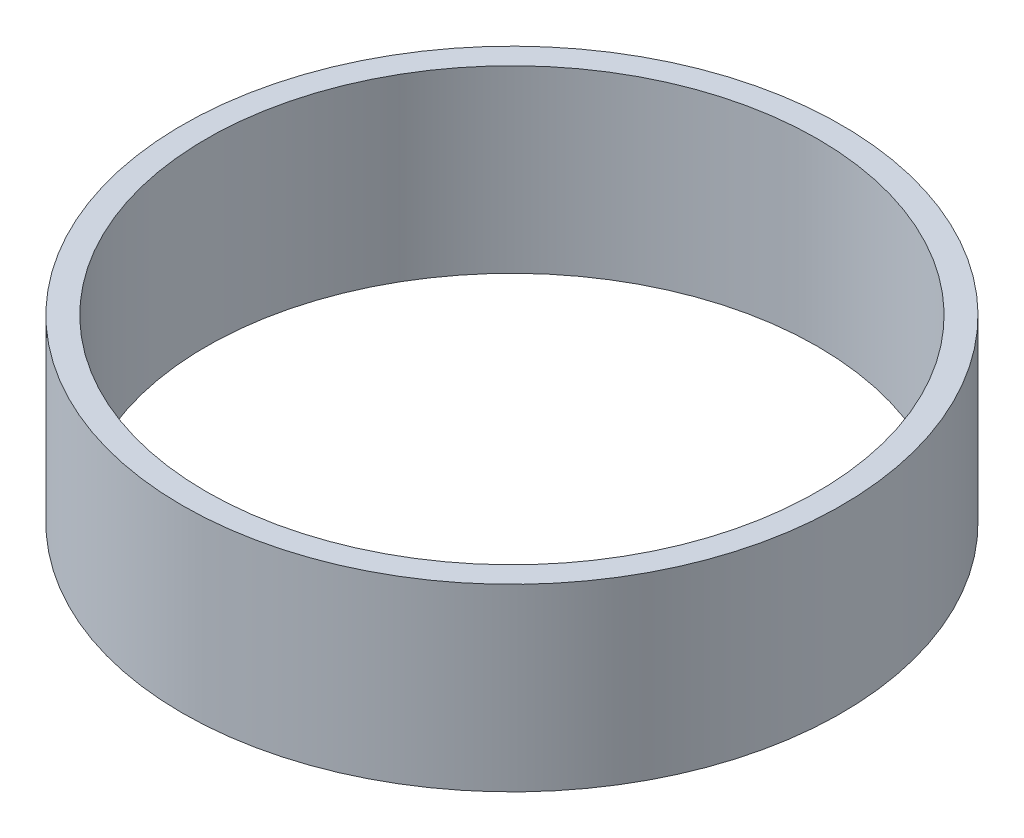
SolidWorks part; units mm, degrees
ref_plane "Front Plane" through (0, 0, 0) normal (0, 0, 1) x (1, 0, 0)
ref_plane "Top Plane" through (0, 0, 0) normal (0, 1, 0) x (1, 0, 0)
ref_plane "Right Plane" through (0, 0, 0) normal (1, 0, 0) x (0, 0, -1)
sketch "Sketch1" plane through (0, 0, 0) normal (0, 1, 0) x (1, 0, 0)
  circle A0 centre (0, 0) radius 10.2
  circle A1 centre (0, 0) radius 11
  dimension "D1" = 20.4
  dimension "D2" = 22
extrude "Boss-Extrude1" add sketch "Sketch1" along normal blind 6
